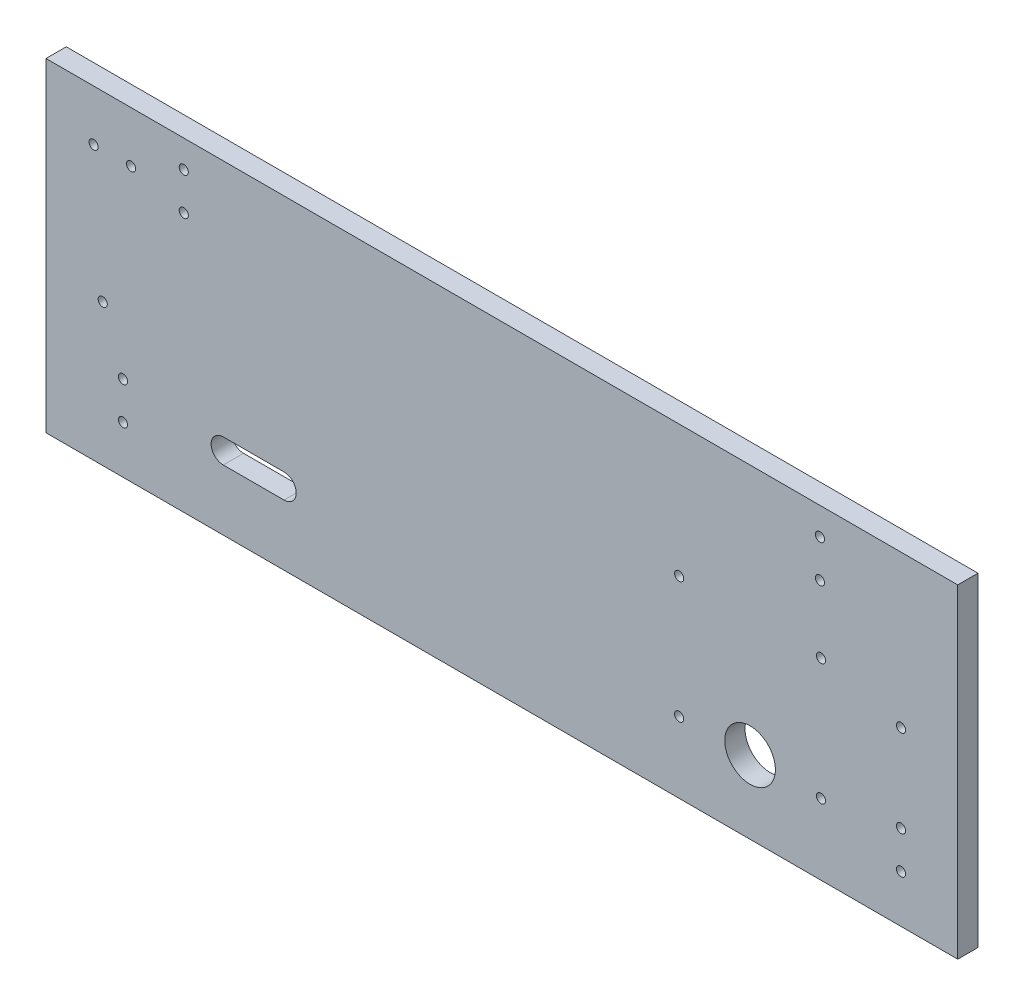
SolidWorks part; units mm, degrees
material "Multistrato di pioppo"
ref_plane "Piano frontale" through (0, 0, 0) normal (0, 0, 1) x (1, 0, 0)
ref_plane "Piano superiore" through (0, 0, 0) normal (0, 1, 0) x (1, 0, 0)
ref_plane "Piano destro" through (0, 0, 0) normal (1, 0, 0) x (0, 0, -1)
sketch "Schizzo1" plane through (0, 0, 0) normal (0, 0, 1) x (1, 0, 0)
  line L1 (0, 0) -> (450, 0)
  line L2 (0, 0) -> (0, 160)
  line L3 (0, 160) -> (450, 160)
  line L4 (450, 0) -> (450, 160)
  dimension "D1" = 450
  dimension "D2" = 160
extrude "Estrusione-Estrusione1" add sketch "Schizzo1" along normal blind 10
sketch "Schizzo2" plane through (0, 0, 10) normal (0, 0, 1) x (1, 0, 0)
  line L0 (102.5, 36) -> (347.5, 36) construction
  line L1 (225, 0) -> (225, 36) construction
  line L2 (0, 0) -> (450, 0) construction
  line L3 (87.5, 36) -> (117.5, 36) construction
  line L4 (87.5, 42) -> (117.5, 42)
  line L5 (87.5, 30) -> (117.5, 30)
  circle A1 centre (347.5, 36) radius 12.5
  arc A2 (87.5, 42) -> (87.5, 30) centre (87.5, 36) ccw
  arc A3 (117.5, 30) -> (117.5, 42) centre (117.5, 36) ccw
  circle A8 centre (68, 146.5) radius 2.25
  circle A9 centre (68, 128) radius 2.25
  circle A10 centre (382, 146.5) radius 2.25
  circle A11 centre (382, 128) radius 2.25
  circle A12 centre (38, 42) radius 2.25
  circle A13 centre (38, 23.5) radius 2.25
  circle A14 centre (422, 42) radius 2.25
  circle A15 centre (422, 23.5) radius 2.25
  circle A16 centre (23.5, 134.9337) radius 2.25
  circle A17 centre (42, 134.9337) radius 2.25
  circle A18 centre (28, 70) radius 2.25
  circle A19 centre (422, 85) radius 2.25
  circle A20 centre (312.5, 95) radius 2.25
  circle A21 centre (382.5, 95) radius 2.25
  circle A22 centre (382.5, 35) radius 2.25
  circle A23 centre (312.5, 35) radius 2.25
  point P9 (102.5, 36)
  dimension "D2" = 25
  dimension "D3" = 12
  dimension "D5" = 30
  dimension "D6" = 4.5
  dimension "D17" = 4.5
  dimension "D18" = 4.5
  dimension "D1" = 36
  dimension "D4" = 245
extrude "Taglio-Estrusione1" cut sketch "Schizzo2" against normal blind 10
